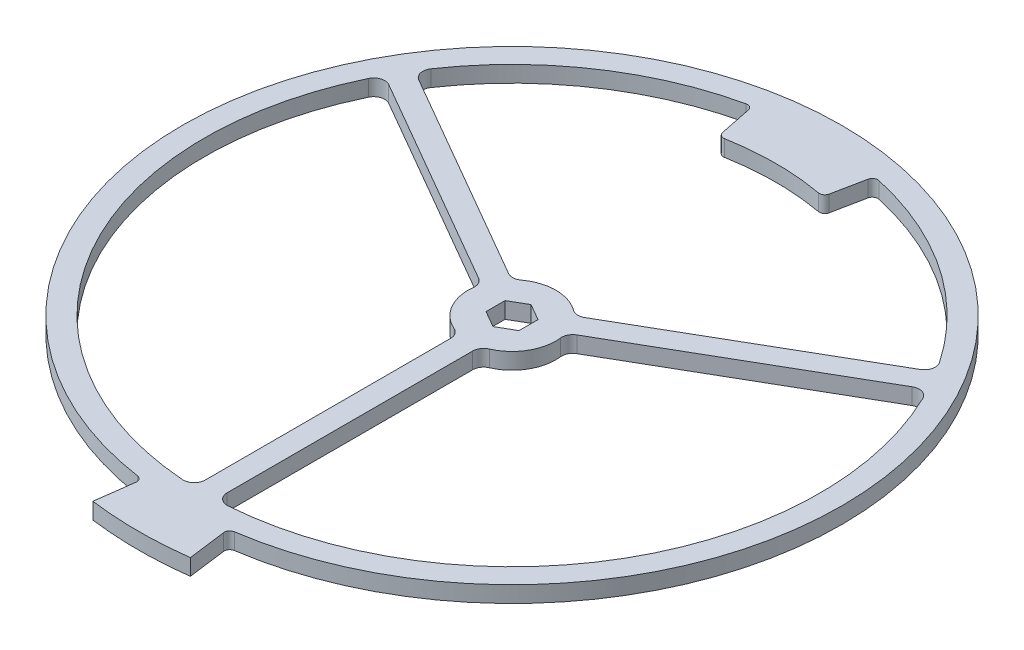
SolidWorks part; units mm, degrees
material "Plain Carbon Steel"
ref_plane "Front Plane" through (0, 0, 0) normal (0, 0, 1) x (1, 0, 0)
ref_plane "Top Plane" through (0, 0, 0) normal (0, 1, 0) x (1, 0, 0)
ref_plane "Right Plane" through (0, 0, 0) normal (1, 0, 0) x (0, 0, -1)
sketch "Sketch1" plane through (0, 0, 0) normal (0, 1, 0) x (1, 0, 0)
  circle A0 centre (0, 0) radius 95.25
  circle A1 centre (0, 0) radius 88.9
  dimension "D1" = 190.5
  dimension "D2" = 6.35
extrude "Boss-Extrude1" add sketch "Sketch1" along normal blind 4.699
sketch "Sketch2" plane through (0, 0, 0) normal (0, -1, 0) x (1, 0, 0)
  line L0 (0, -88.9) -> (0, -76.2) construction
  line L1 (0, 107.95) -> (0, 95.25) construction
  line L2 (-14.0903, 107.0265) -> (-12.4326, 94.4351)
  line L3 (-17.6098, -87.1384) -> (-15.0941, -74.6901)
  line L4 (12.4326, 94.4351) -> (14.0903, 107.0265)
  line L6 (15.0941, -74.6901) -> (17.6098, -87.1384)
  circle A0 centre (0, 0) radius 107.95 construction
  circle A1 centre (0, 0) radius 76.2 construction
  circle A2 centre (0, 0) radius 88.9 construction
  circle A4 centre (0, 0) radius 95.25 construction
  arc A5 (-14.0903, 107.0265) -> (14.0903, 107.0265) centre (0, 0) cw
  arc A6 (-15.0941, -74.6901) -> (15.0941, -74.6901) centre (0, 0) ccw
  circle M1 centre (0, 0) radius 95.25
  circle M2 centre (0, 0) radius 88.9
  dimension "D1" = 12.7
  dimension "D2" = 215.9
  dimension "D3" = 15
  dimension "D4" = 22.85
extrude "Boss-Extrude2" add sketch "Sketch2" against normal up to surface (4.699 mm away) contours A6 L3 L6 M2 | A5 L2 L4 M1
sketch "Sketch3" plane through (0, 0, 0) normal (0, -1, 0) x (1, 0, 0)
  line L1 (0, 5.4993) -> (-4.7625, 2.7496)
  line L2 (-4.7625, 2.7496) -> (-4.7625, -2.7496)
  line L3 (-4.7625, -2.7496) -> (0, -5.4993)
  line L4 (0, -5.4993) -> (4.7625, -2.7496)
  line L5 (4.7625, -2.7496) -> (4.7625, 2.7496)
  line L6 (4.7625, 2.7496) -> (0, 5.4993)
  circle A0 centre (0, 0) radius 12.7
  circle A2 centre (0, 0) radius 4.7625 construction
  dimension "D1" = 25.4
  dimension "D2" = 9.525
extrude "Boss-Extrude3" add sketch "Sketch3" against normal up to surface (4.699 mm away) separate body up to face at (0, 4.699, 53.5404)
sketch "Sketch4" plane through (0, 0, 0) normal (0, -1, 0) x (-1, 0, 0)
  line L0 (0, -88.9) -> (0, -12.7) construction
  line L1 (3.175, -88.8433) -> (3.175, -12.2967)
  line L2 (-3.175, -88.8433) -> (-3.175, -12.2967)
  arc A0 (-17.6098, 87.1384) -> (17.6098, 87.1384) centre (0, 0) ccw construction
  circle A1 centre (0, 0) radius 12.7 construction
  arc A3 (3.175, -12.2967) -> (-3.175, -12.2967) centre (0, 0) cw
  arc A4 (3.175, -88.8433) -> (-3.175, -88.8433) centre (0, 0) cw
  dimension "D1" = 6.35
extrude "Boss-Extrude4" add sketch "Sketch4" against normal up to surface (4.699 mm away) up to face at (0, 4.699, 12.7)
fillet "Fillet1" radius 3.175 4 edges at (-3.175, 2.3495, 12.2967) (3.175, 2.3495, 12.2967) (3.175, 2.3495, 88.8433) (-3.175, 2.3495, 88.8433)
pattern_circular "CirPattern1" count 3 over 360 about axis through (0, 0, 0) along (0, 1, 0) of "Boss-Extrude4", "Fillet1"
fillet "Fillet2" radius 1.5875 6 edges at (-17.6098, 2.3495, -87.1384) (17.6098, 2.3495, -87.1384) (12.4326, 2.3495, 94.4351) (-12.4326, 2.3495, 94.4351) (15.0941, 2.3495, -74.6901) (-15.0941, 2.3495, -74.6901)
